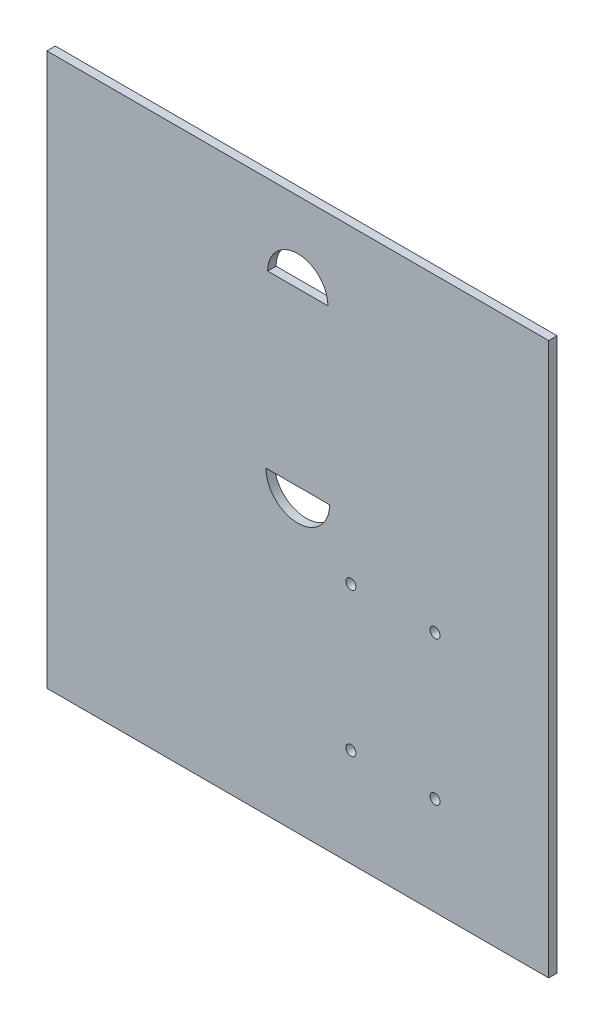
SolidWorks part; units mm, degrees
ref_plane "Plan de face" through (0, 0, 0) normal (0, 0, 1) x (1, 0, 0)
ref_plane "Plan de dessus" through (0, 0, 0) normal (0, 1, 0) x (1, 0, 0)
ref_plane "Plan de droite" through (0, 0, 0) normal (1, 0, 0) x (0, 0, -1)
sketch "Sketch1" plane through (0, 0, 0) normal (0, 0, 1) x (1, 0, 0)
  line L1 (-220.2282, 110.1141) -> (29.7718, 110.1141)
  line L2 (-220.2282, 110.1141) -> (-220.2282, -164.8859)
  line L3 (-220.2282, -164.8859) -> (29.7718, -164.8859)
  line L4 (29.7718, 110.1141) -> (29.7718, -164.8859)
  dimension "D1" = 275
  dimension "D2" = 250
extrude "Boss-Extrude1" add sketch "Sketch1" along normal blind 4.2
sketch "Esquisse1" plane through (0, 0, 4.2) normal (0, 0, 1) x (1, 0, 0)
  line L0 (-220.2282, 110.1141) -> (-220.2282, -164.8859) construction
  line L1 (-110.2282, 70.1141) -> (-80.2282, 70.1141)
  line L2 (29.7718, 110.1141) -> (-220.2282, 110.1141) construction
  line L5 (-111.0739, -15.3059) -> (-79.3825, -15.3059)
  arc A1 (-110.2282, 70.1141) -> (-80.2282, 70.1141) centre (-95.2282, 70.1141) cw
  arc A3 (-111.0739, -15.3059) -> (-79.3825, -15.3059) centre (-95.2282, -15.3059) ccw
  circle A4 centre (-68.7685, -115.9436) radius 2.5
  circle A5 centre (-26.8585, -115.9436) radius 2.5
  circle A6 centre (-68.7685, -44.1886) radius 2.5
  circle A7 centre (-26.8585, -44.1886) radius 2.5
  dimension "D2" = 15
  dimension "D4" = 85.42
  dimension "D1" = 125
  dimension "D3" = 40
  dimension "D5" = 0
  dimension "D6" = 41.91
  dimension "D7" = 71.755
  dimension "D8" = 41.91
  dimension "D9" = 71.755
  dimension "D10" = 83.0977
  dimension "D11" = 83.0977
extrude "Enlèv. mat.-Extru.1" cut sketch "Esquisse1" against normal through all
